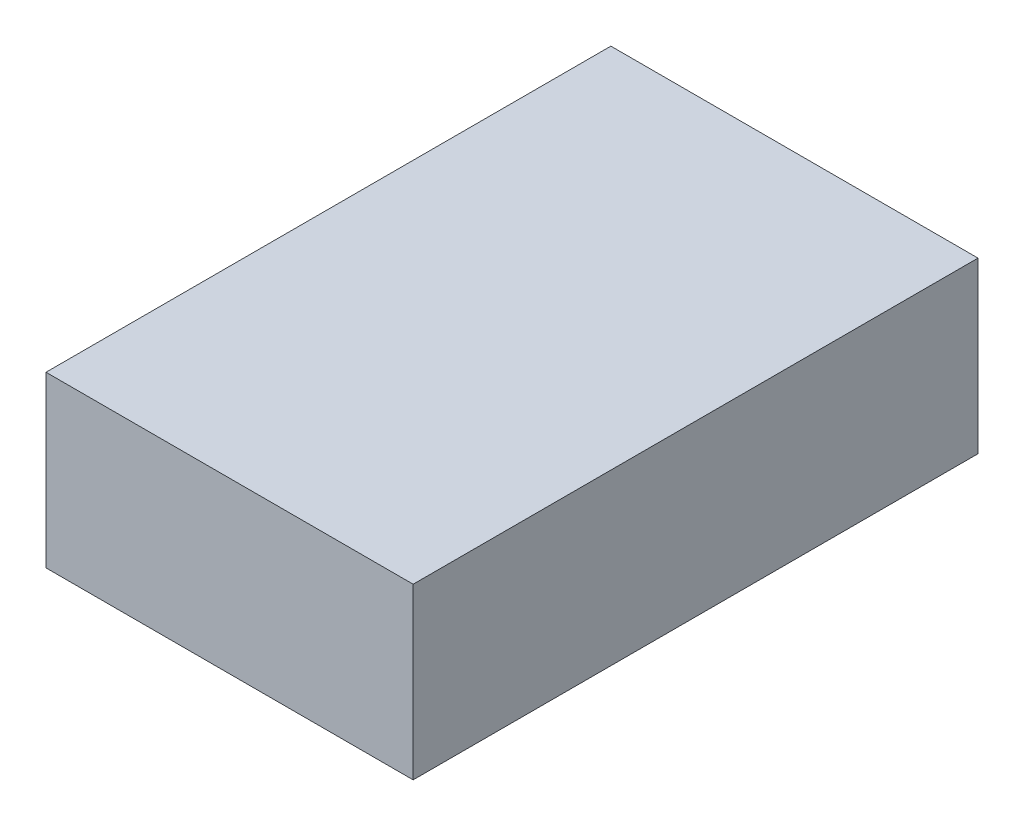
SolidWorks part; units mm, degrees
ref_plane "Front Plane" through (0, 0, 0) normal (0, 0, 1) x (1, 0, 0)
ref_plane "Top Plane" through (0, 0, 0) normal (0, 1, 0) x (1, 0, 0)
ref_plane "Right Plane" through (0, 0, 0) normal (1, 0, 0) x (0, 0, -1)
sketch "Sketch2" plane through (0, 0, 0) normal (0, 1, 0) x (1, 0, 0)
  line L1 (0, 0) -> (165.1, 0)
  line L2 (0, 0) -> (0, 254)
  line L3 (0, 254) -> (165.1, 254)
  line L4 (165.1, 0) -> (165.1, 254)
  dimension "D1" = 165.1
  dimension "D2" = 254
extrude "Boss-Extrude1" add sketch "Sketch2" along normal blind 76.2 contours L2 L1 L4 L3
